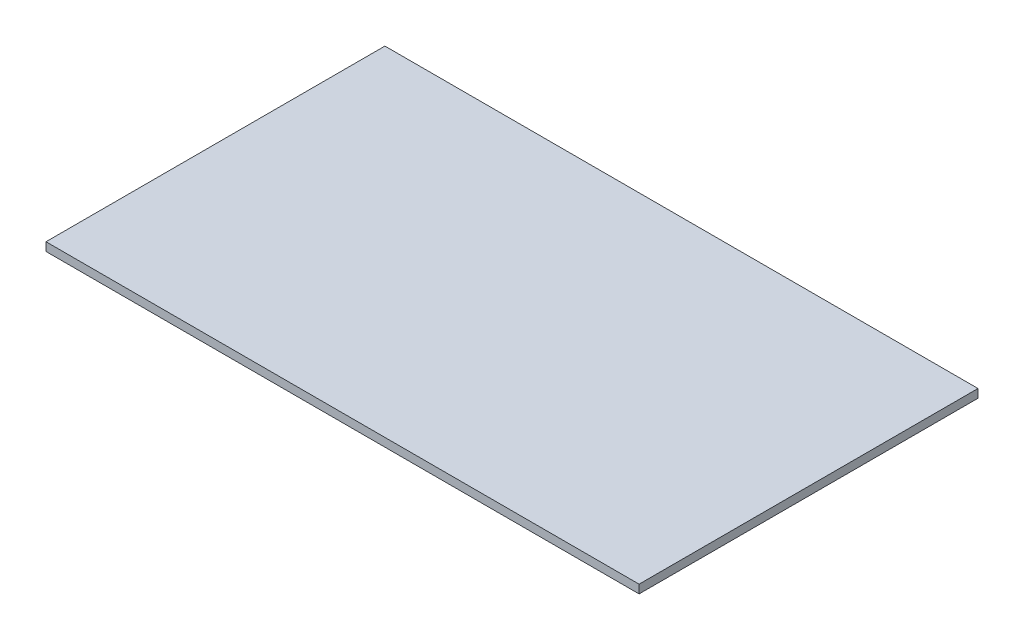
SolidWorks part; units mm, degrees
ref_plane "Front Plane" through (0, 0, 0) normal (0, 0, 1) x (1, 0, 0)
ref_plane "Top Plane" through (0, 0, 0) normal (0, 1, 0) x (1, 0, 0)
ref_plane "Right Plane" through (0, 0, 0) normal (1, 0, 0) x (0, 0, -1)
sketch "Sketch1" plane through (0, 0, 0) normal (0, 1, 0) x (1, 0, 0)
  line L1 (-175, 100) -> (175, 100)
  line L2 (-175, 100) -> (-175, -100)
  line L3 (-175, -100) -> (175, -100)
  line L4 (175, 100) -> (175, -100)
  line L5 (-175, 100) -> (175, -100) construction
  line L6 (-175, -100) -> (175, 100) construction
  point P0 (0, 0)
  dimension "D1" = 350
  dimension "D2" = 200
extrude "Boss-Extrude1" add sketch "Sketch1" along normal blind 5
